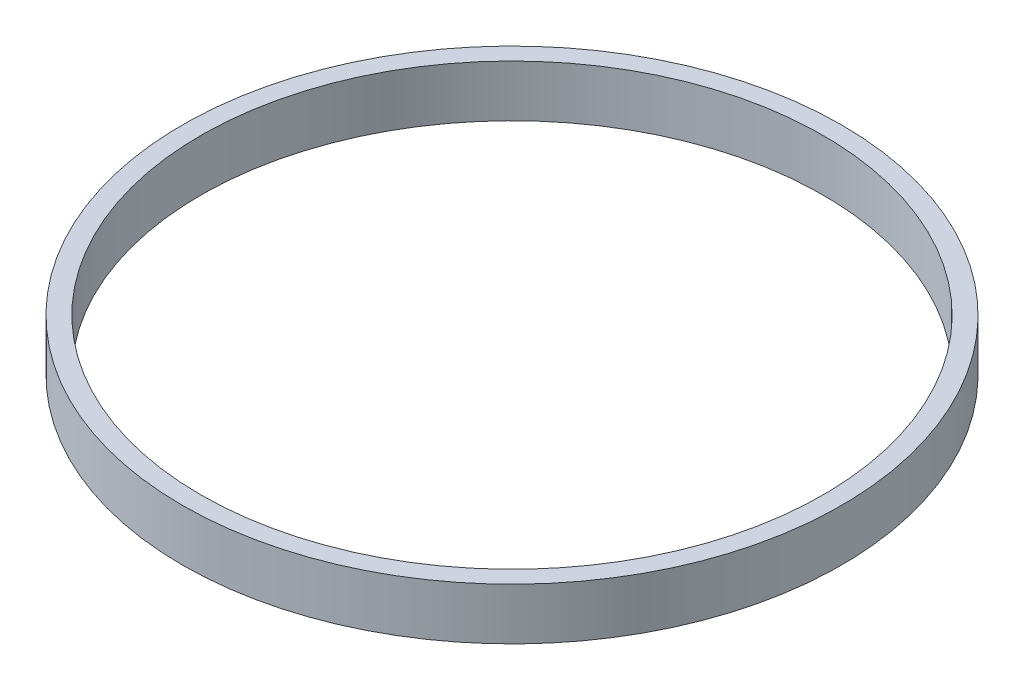
SolidWorks part; units mm, degrees
material "ABS"
ref_plane "Front Plane" through (0, 0, 0) normal (0, 0, 1) x (1, 0, 0)
ref_plane "Top Plane" through (0, 0, 0) normal (0, 1, 0) x (1, 0, 0)
ref_plane "Right Plane" through (0, 0, 0) normal (1, 0, 0) x (0, 0, -1)
sketch "Sketch2" plane through (0, 0, 0) normal (0, 1, 0) x (1, 0, 0)
  circle A0 centre (0, 0) radius 34
  circle A1 centre (0, 0) radius 36
  dimension "D1" = 68
  dimension "D2" = 72
extrude "Boss-Extrude1" add sketch "Sketch2" along normal blind 5.65
equation "\"L1L\"=500"
equation "\"L1Thick\"=6.35"
equation "\"Harm-Drive-Outer\"=74.5"
equation "\"L1-Spacing\"=115.65"
equation "\"L-Bracket-HoleToWall\"=12.5"
equation "\"L-Bracket-HoleToSide\"=11"
equation "\"Bracket-Hole-D\"=6.8"
